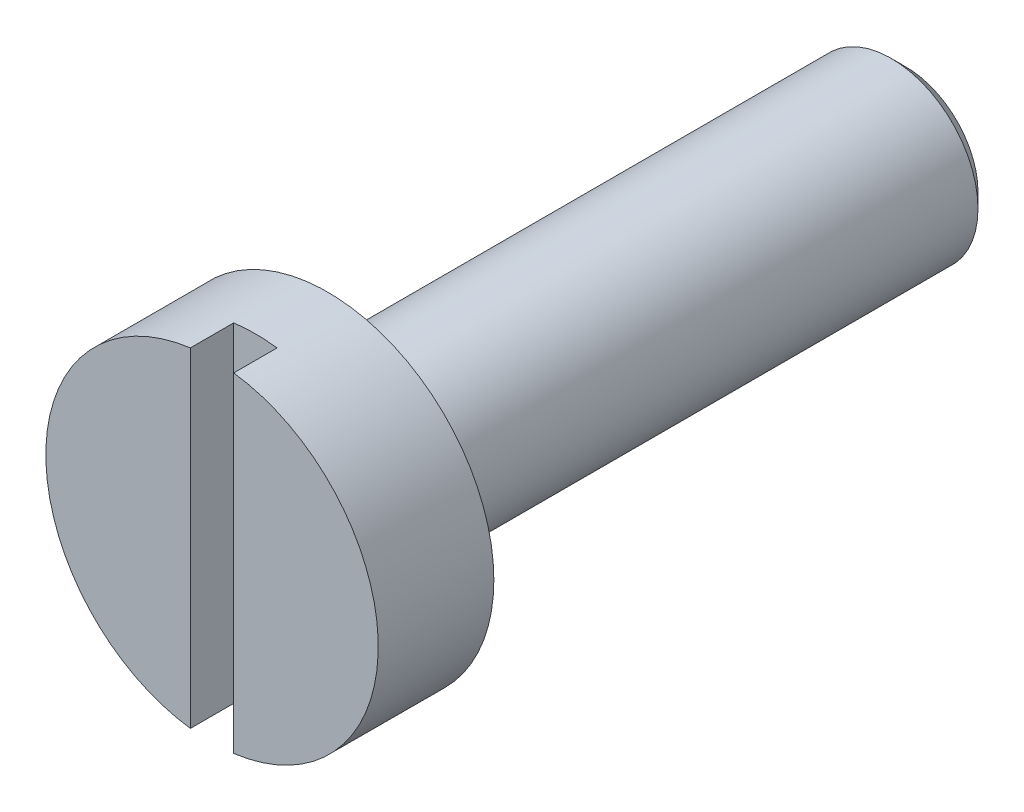
SolidWorks part; units mm, degrees
ref_plane "Спереди" through (0, 0, 0) normal (0, 0, 1) x (1, 0, 0)
ref_plane "Сверху" through (0, 0, 0) normal (0, 1, 0) x (1, 0, 0)
ref_plane "Справа" through (0, 0, 0) normal (1, 0, 0) x (0, 0, -1)
sketch "Эскиз1" plane through (0, 0, 0) normal (0, 0, 1) x (1, 0, 0)
  circle A0 centre (0, 0) radius 1.15
extrude "Бобышка-Вытянуть1" add sketch "Эскиз1" along normal blind 0.8
sketch "Эскиз2" plane through (0, 0, 0) normal (0, 0, 1) x (1, 0, 0)
  circle A0 centre (0, 0) radius 0.6
extrude "Бобышка-Вытянуть2" add sketch "Эскиз2" against normal blind 4
chamfer "Фаска1" distance 0.1 angle 45 1 edges at (0.6, 0, -4)
sketch "Эскиз3" plane through (0, 0, 0.8) normal (0, 0, 1) x (1, 0, 0)
  line L1 (0.15, -1.1946) -> (-0.15, -1.1946)
  line L2 (0.15, -1.1946) -> (0.15, 1.1946)
  line L3 (0.15, 1.1946) -> (-0.15, 1.1946)
  line L4 (-0.15, -1.1946) -> (-0.15, 1.1946)
  line L5 (0.15, -1.1946) -> (-0.15, 1.1946) construction
  line L6 (0.15, 1.1946) -> (-0.15, -1.1946) construction
  point P0 (0, 0)
extrude "Вырез-Вытянуть1" cut sketch "Эскиз3" against normal blind 0.3
